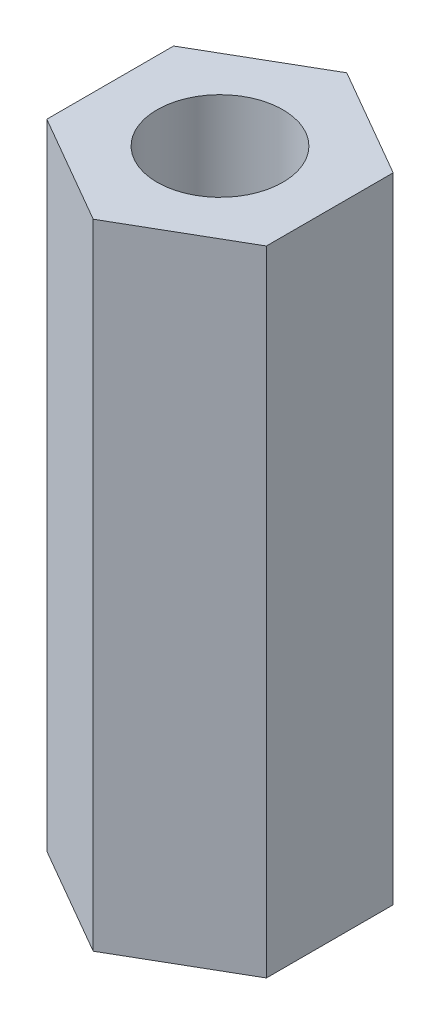
SolidWorks part; units mm, degrees
ref_plane "Front Plane" through (0, 0, 0) normal (0, 0, 1) x (1, 0, 0)
ref_plane "Top Plane" through (0, 0, 0) normal (0, 1, 0) x (1, 0, 0)
ref_plane "Right Plane" through (0, 0, 0) normal (1, 0, 0) x (0, 0, -1)
sketch "Sketch2" plane through (0, 0, 0) normal (0, 1, 0) x (1, 0, 0)
  line L1 (0, 16) -> (-13.8564, 8)
  line L2 (-13.8564, 8) -> (-13.8564, -8)
  line L3 (-13.8564, -8) -> (0, -16)
  line L4 (0, -16) -> (13.8564, -8)
  line L5 (13.8564, -8) -> (13.8564, 8)
  line L6 (13.8564, 8) -> (0, 16)
  circle A0 centre (0, 0) radius 13.8564 construction
  circle A1 centre (0, 0) radius 7.9375
  dimension "D1" = 15.875
  dimension "D2" = 16
extrude "Boss-Extrude1" add sketch "Sketch2" along normal blind 80
equation "\"internalDiameter\"= 5in / 8"
equation "\"D1@Sketch2\"=\"internalDiameter\""
equation "\"nutDepth\"= 80mm"
equation "\"D1@Boss-Extrude1\"=\"nutDepth\""
